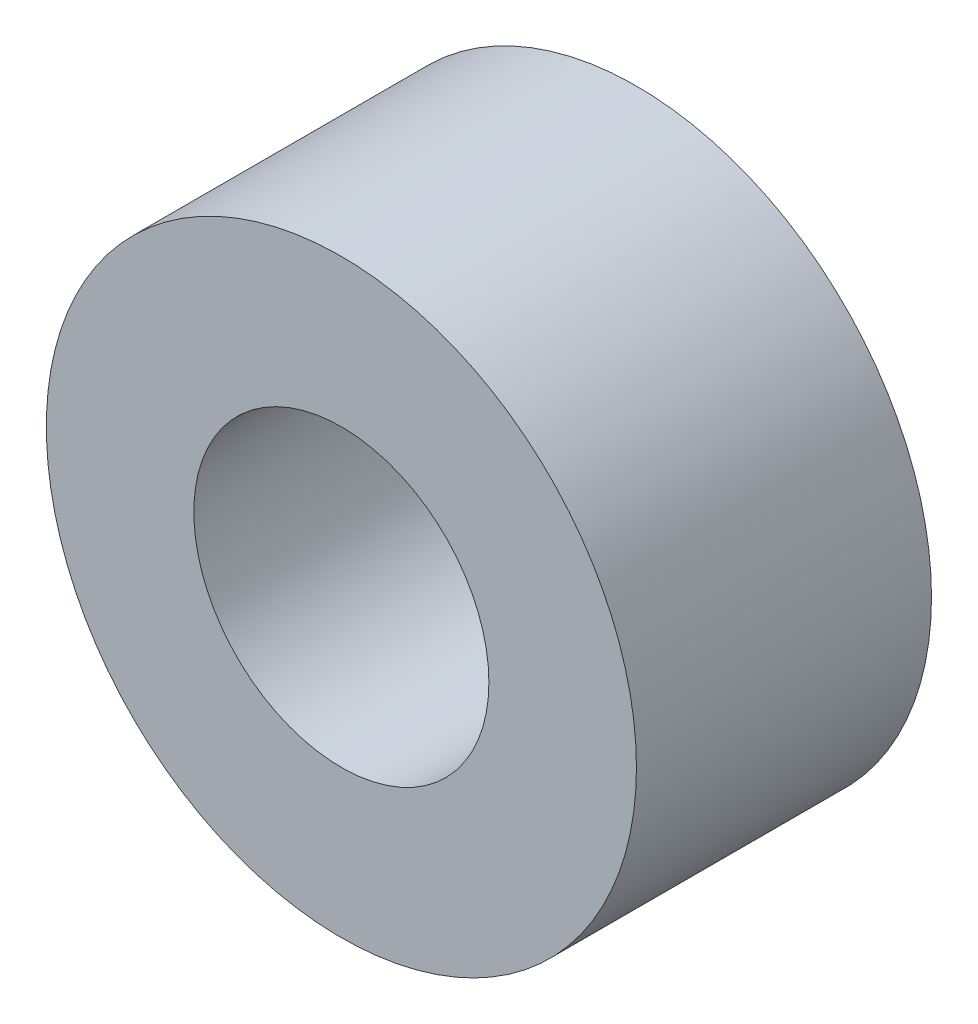
SolidWorks part; units mm, degrees
ref_plane "Front" through (0, 0, 0) normal (0, 0, 1) x (1, 0, 0)
ref_plane "Top" through (0, 0, 0) normal (0, 1, 0) x (1, 0, 0)
ref_plane "Right" through (0, 0, 0) normal (1, 0, 0) x (0, 0, -1)
sketch "Sketch1" plane through (0, 0, 0) normal (0, 0, 1) x (1, 0, 0)
  circle A0 centre (-43.1601, -91.7569) radius 3.175
  circle A1 centre (-43.1601, -91.7569) radius 1.5875
  dimension "D1" = 3.175
  dimension "D2" = 6.35
extrude "Boss-Extrude1" add sketch "Sketch1" along normal mid plane 3.175
